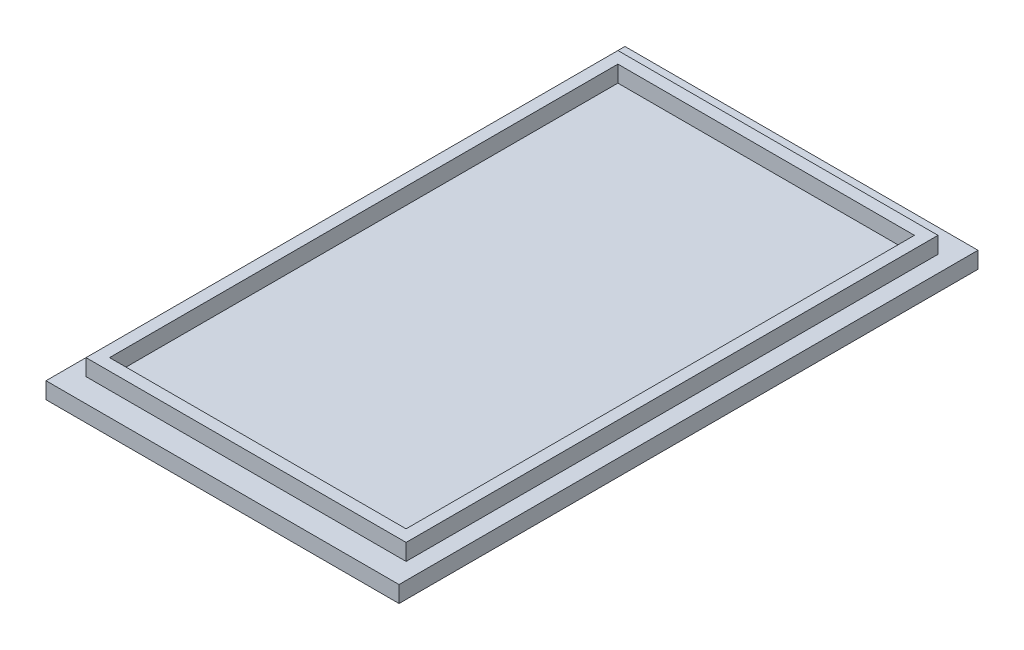
SolidWorks part; units mm, degrees
ref_plane "Front Plane" through (0, 0, 0) normal (0, 0, 1) x (1, 0, 0)
ref_plane "Top Plane" through (0, 0, 0) normal (0, 1, 0) x (1, 0, 0)
ref_plane "Right Plane" through (0, 0, 0) normal (1, 0, 0) x (0, 0, -1)
sketch "Sketch1" plane through (0, 0, 0) normal (0, 1, 0) x (1, 0, 0)
  line L1 (-175.6426, -124.0686) -> (-138.1426, -124.0686)
  line L2 (-175.6426, -124.0686) -> (-175.6426, -62.5686)
  line L3 (-175.6426, -62.5686) -> (-138.1426, -62.5686)
  line L4 (-138.1426, -124.0686) -> (-138.1426, -62.5686)
  dimension "D1" = 61.5
  dimension "D2" = 37.5
extrude "Boss-Extrude1" add sketch "Sketch1" along normal blind 1.75
sketch "Sketch2" plane through (0, 1.75, 0) normal (0, 1, 0) x (1, 0, 0)
  line L0 (-138.1426, -124.0686) -> (-138.1426, -62.5686) construction
  line L1 (-173.8926, -121.5686) -> (-139.8926, -121.5686)
  line L2 (-173.8926, -121.5686) -> (-173.8926, -65.0686)
  line L3 (-173.8926, -65.0686) -> (-139.8926, -65.0686)
  line L4 (-139.8926, -121.5686) -> (-139.8926, -65.0686)
  line L6 (-175.6426, -124.0686) -> (-138.1426, -124.0686) construction
  dimension "D1" = 56.5
  dimension "D2" = 34
  dimension "D3" = 1.75
  dimension "D4" = 2.5
extrude "Boss-Extrude2" add sketch "Sketch2" along normal blind 1.75
sketch "Sketch3" plane through (0, 3.5, 0) normal (0, 1, 0) x (1, 0, 0)
  line L0 (-139.8926, -65.0686) -> (-173.8926, -65.0686) construction
  line L1 (-172.6426, -120.3186) -> (-141.1426, -120.3186)
  line L2 (-172.6426, -120.3186) -> (-172.6426, -66.3186)
  line L3 (-172.6426, -66.3186) -> (-141.1426, -66.3186)
  line L4 (-141.1426, -120.3186) -> (-141.1426, -66.3186)
  line L5 (-139.8926, -121.5686) -> (-139.8926, -65.0686) construction
  line L6 (-173.8926, -121.5686) -> (-139.8926, -121.5686) construction
  line L7 (-173.8926, -65.0686) -> (-173.8926, -121.5686) construction
  dimension "D1" = 1.25
  dimension "D2" = 1.25
  dimension "D3" = 1.25
  dimension "D4" = 1.25
extrude "Cut-Extrude1" cut sketch "Sketch3" against normal blind 1.75
